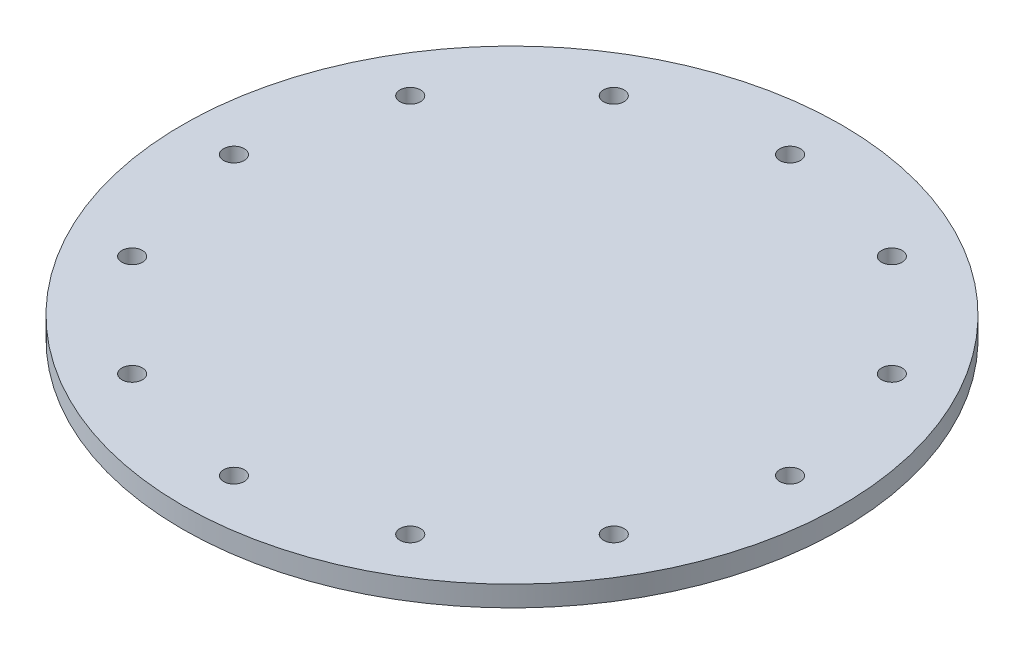
SolidWorks part; units mm, degrees
ref_plane "Front Plane" through (0, 0, 0) normal (0, 0, 1) x (1, 0, 0)
ref_plane "Top Plane" through (0, 0, 0) normal (0, 1, 0) x (1, 0, 0)
ref_plane "Right Plane" through (0, 0, 0) normal (1, 0, 0) x (0, 0, -1)
sketch "Sketch1" plane through (0, 0, 0) normal (0, 1, 0) x (1, 0, 0)
  circle A0 centre (0, 0) radius 101.6
  dimension "D1" = 203.2
extrude "Boss-Extrude1" add sketch "Sketch1" along normal blind 6.35
sketch "Sketch2" plane through (0, 6.35, 0) normal (0, 1, 0) x (1, 0, 0)
  circle A0 centre (0, 0) radius 63.5
  dimension "D1" = 127
sketch "Sketch3" plane through (0, 6.35, 0) normal (0, 1, 0) x (1, 0, 0)
  circle A0 centre (0, 0) radius 69.85
  circle A1 centre (0, 0) radius 85.725
  circle A2 centre (0, 85.725) radius 3.175
  circle A3 centre (42.8625, 74.24) radius 3.175
  circle A4 centre (74.24, 42.8625) radius 3.175
  circle A5 centre (85.725, 0) radius 3.175
  circle A6 centre (74.24, -42.8625) radius 3.175
  circle A7 centre (42.8625, -74.24) radius 3.175
  circle A8 centre (0, -85.725) radius 3.175
  circle A9 centre (-42.8625, -74.24) radius 3.175
  circle A10 centre (-74.24, -42.8625) radius 3.175
  circle A11 centre (-85.725, 0) radius 3.175
  circle A12 centre (-74.24, 42.8625) radius 3.175
  circle A13 centre (-42.8625, 74.24) radius 3.175
  point P30 (0, 0)
  dimension "D1" = 139.7
  dimension "D2" = 15.875
  dimension "D3" = 6.35
  dimension "D4" = 12
extrude "Cut-Extrude2" cut sketch "Sketch3" against normal up to next contours A12 | A13 | A3 | A4 | A5 | A6 | A7 | A8 | A9 | A10 | A11 | A2
equation "\"od\"=8"
equation "\"D1@Sketch1\"=\"od\""
equation "\"gw\"= 0.158'groove width for O-ring"
equation "\"gd\"= .101'groove depth for O-ring"
